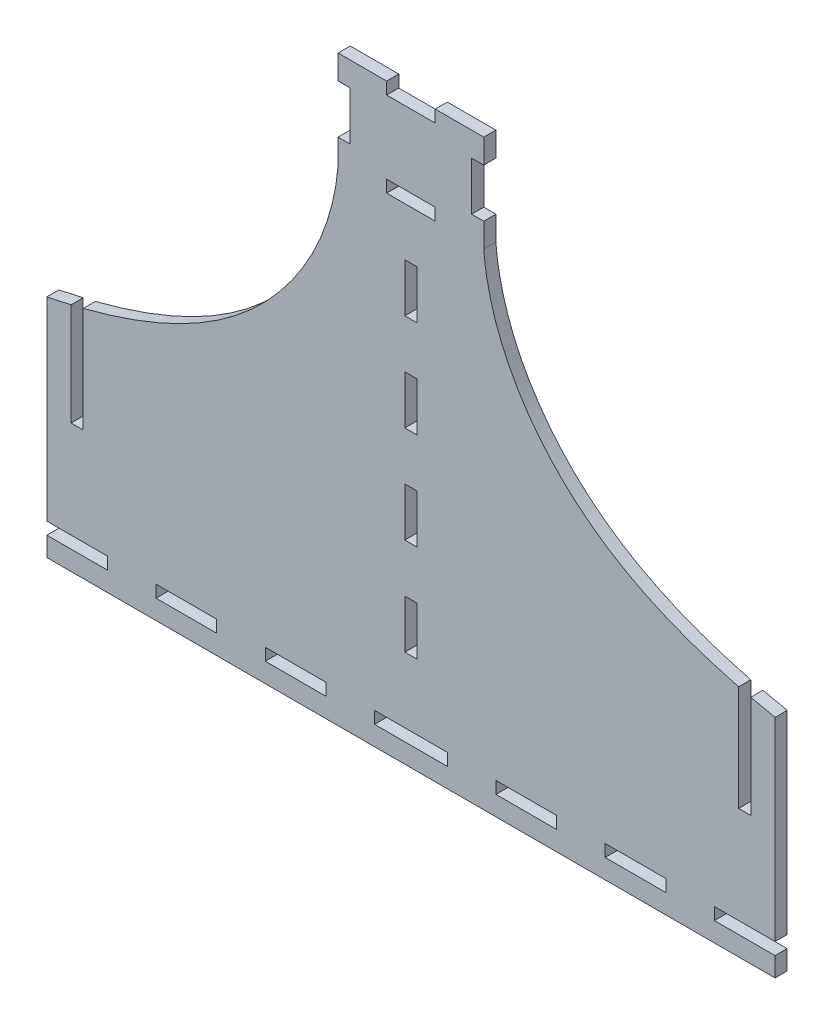
SolidWorks part; units mm, degrees
ref_plane "Front Plane" through (0, 0, 0) normal (0, 0, 1) x (1, 0, 0)
ref_plane "Top Plane" through (0, 0, 0) normal (0, 1, 0) x (1, 0, 0)
ref_plane "Right Plane" through (0, 0, 0) normal (1, 0, 0) x (0, 0, -1)
sketch "Sketch1" plane through (0, 0, 0) normal (0, 0, 1) x (1, 0, 0)
  line L0 (-39.7844, 125.4532) -> (-39.7844, 135.4532)
  line L1 (-39.7844, 165.4532) -> (-59.7844, 165.4532)
  line L2 (-99.7844, 125.4532) -> (-99.7844, 135.4532)
  line L3 (-79.7844, 165.4532) -> (-99.7844, 165.4532)
  line L5 (-79.7844, 165.4532) -> (-79.7844, 160.4532)
  line L6 (-79.7844, 160.4532) -> (-59.7844, 160.4532)
  line L7 (-59.7844, 165.4532) -> (-59.7844, 160.4532)
  line L8 (-69.7844, 165.4532) -> (-59.7844, 160.4532) construction
  line L9 (-79.7844, 160.4532) -> (-69.7844, 165.4532) construction
  line L10 (-39.7844, 155.4532) -> (-39.7844, 165.4532)
  line L11 (-39.7844, 155.4532) -> (-44.7844, 155.4532)
  line L13 (-39.7844, 135.4532) -> (-44.7844, 135.4532)
  line L14 (-44.7844, 155.4532) -> (-44.7844, 135.4532)
  line L15 (-94.7844, 155.4532) -> (-94.7844, 135.4532)
  line L16 (-99.7844, 135.4532) -> (-94.7844, 135.4532)
  line L17 (-99.7844, 155.4532) -> (-94.7844, 155.4532)
  line L18 (-99.7844, 155.4532) -> (-99.7844, 165.4532)
  line L19 (-94.7844, 145.4532) -> (-90.6665, 145.4532) construction
  line L20 (-79.7844, 130.4532) -> (-69.7844, 125.4532) construction
  line L21 (-69.7844, 125.4532) -> (-59.7844, 130.4532) construction
  line L22 (-59.7844, 125.4532) -> (-59.7844, 130.4532)
  line L23 (-79.7844, 130.4532) -> (-59.7844, 130.4532)
  line L24 (-79.7844, 125.4532) -> (-79.7844, 130.4532)
  line L25 (-79.7844, 125.4532) -> (-59.7844, 125.4532)
  line L26 (-72.2844, 65.4532) -> (-67.2844, 65.4532)
  line L27 (-72.2844, 105.4532) -> (-67.2844, 105.4532)
  line L28 (80.2156, -61.5468) -> (55.2156, -61.5468)
  line L29 (55.2156, -61.5468) -> (55.2156, -66.5468)
  line L30 (55.2156, -66.5468) -> (80.2156, -66.5468)
  line L32 (35.2156, -61.5468) -> (10.2156, -61.5468)
  line L33 (10.2156, -61.5468) -> (10.2156, -66.5468)
  line L34 (10.2156, -66.5468) -> (35.2156, -66.5468)
  line L35 (35.2156, -66.5468) -> (35.2156, -61.5468)
  line L36 (-9.7844, -61.5468) -> (-34.7844, -61.5468)
  line L37 (-34.7844, -61.5468) -> (-34.7844, -66.5468)
  line L38 (-34.7844, -66.5468) -> (-9.7844, -66.5468)
  line L39 (-9.7844, -66.5468) -> (-9.7844, -61.5468)
  line L40 (-54.7844, -61.5468) -> (-84.7844, -61.5468)
  line L41 (-84.7844, -61.5468) -> (-84.7844, -66.5468)
  line L42 (-84.7844, -66.5468) -> (-54.7844, -66.5468)
  line L43 (-54.7844, -66.5468) -> (-54.7844, -61.5468)
  line L44 (-104.7844, -61.5468) -> (-129.7844, -61.5468)
  line L45 (-129.7844, -61.5468) -> (-129.7844, -66.5468)
  line L46 (-129.7844, -66.5468) -> (-104.7844, -66.5468)
  line L47 (-104.7844, -66.5468) -> (-104.7844, -61.5468)
  line L48 (-149.7844, -61.5468) -> (-174.7844, -61.5468)
  line L49 (-174.7844, -61.5468) -> (-174.7844, -66.5468)
  line L50 (-174.7844, -66.5468) -> (-149.7844, -66.5468)
  line L51 (-149.7844, -66.5468) -> (-149.7844, -61.5468)
  line L52 (-194.7844, -61.5468) -> (-219.7844, -61.5468)
  line L54 (-219.7844, -66.5468) -> (-194.7844, -66.5468)
  line L55 (-194.7844, -66.5468) -> (-194.7844, -61.5468)
  line L56 (-69.7844, -61.5468) -> (-69.7844, -38.2904) construction
  line L57 (-219.7844, -66.5468) -> (-219.7844, -74.5468)
  line L59 (-219.7844, 18.4532) -> (-219.7844, -61.5468)
  line L60 (-219.7844, -74.5468) -> (80.2156, -74.5468)
  line L61 (80.2156, 18.4532) -> (80.2156, -61.5468)
  line L62 (80.2156, -66.5468) -> (80.2156, -74.5468)
  line L63 (-72.2844, 105.4532) -> (-72.2844, 85.4532)
  line L64 (-72.2844, 85.4532) -> (-67.2844, 85.4532)
  line L65 (-67.2844, 105.4532) -> (-67.2844, 85.4532)
  line L66 (-72.2844, 105.4532) -> (-67.2844, 85.4532) construction
  line L67 (-72.2844, 85.4532) -> (-67.2844, 105.4532) construction
  line L68 (-72.2844, 65.4532) -> (-72.2844, 45.4532)
  line L69 (-67.2844, 65.4532) -> (-67.2844, 45.4532)
  line L70 (-72.2844, 45.4532) -> (-67.2844, 45.4532)
  line L71 (-72.2844, 25.4532) -> (-67.2844, 25.4532)
  line L72 (-72.2844, 25.4532) -> (-72.2844, 5.4532)
  line L73 (-67.2844, 25.4532) -> (-67.2844, 5.4532)
  line L74 (-72.2844, 5.4532) -> (-67.2844, 5.4532)
  line L75 (-72.2844, -14.5468) -> (-67.2844, -14.5468)
  line L76 (-72.2844, -14.5468) -> (-72.2844, -34.5468)
  line L77 (-67.2844, -14.5468) -> (-67.2844, -34.5468)
  line L78 (-72.2844, -34.5468) -> (-67.2844, -34.5468)
  line L80 (70.2156, -21.5468) -> (65.2156, -21.5468)
  line L81 (65.2156, -21.5468) -> (65.2156, 21.8436)
  line L82 (70.2156, -21.5468) -> (70.2156, 20.6184)
  line L83 (-209.7844, -21.5468) -> (-209.7844, 20.6184)
  line L84 (-204.7844, -21.5468) -> (-204.7844, 21.8436)
  line L85 (-209.7844, -21.5468) -> (-204.7844, -21.5468)
  spline S0 degree 2 poles (80.2156, 18.4532) (75.2223, 19.4417) (70.2156, 20.6184) knots 0 0 0 0.059833 0.059833 0.059833
  spline S1 degree 2 poles (-219.7844, 18.4532) (-214.7911, 19.4417) (-209.7844, 20.6184) knots 0 0 0 0.059833 0.059833 0.059833
  spline S2 degree 3 poles (65.2156, 21.8436) (57.9374, 23.7019) (35.9058, 30.3485) (-11.4217, 54.2754) (-37.385, 95.2098) (-39.7844, 125.4532) knots 0.089716 0.089716 0.089716 0.089716 0.220284 0.486407 1 1 1 1
  spline S3 degree 3 poles (-204.7844, 21.8436) (-197.5062, 23.7019) (-175.4746, 30.3485) (-128.1471, 54.2754) (-102.1839, 95.2098) (-99.7844, 125.4532) knots 0.089716 0.089716 0.089716 0.089716 0.220284 0.486407 1 1 1 1
  point P14 (-69.7844, 165.4532)
  point P38 (0, 0)
  point P46 (-69.7844, 165.4532)
  point P66 (-69.7844, 125.4532)
  point P67 (-69.7844, 125.4532)
  point P68 (-69.7844, 95.4532)
  dimension "D1" = 300
  dimension "D2" = 8
  dimension "D3" = 80
  dimension "D4" = 40
  dimension "D5" = 30
  dimension "D6" = 240
  dimension "D7" = 20
  dimension "D8" = 5
  dimension "D9" = 5
  dimension "D10" = 20
  dimension "D11" = 10
  dimension "D12" = 25
  dimension "D13" = 10
  dimension "D14" = 5
  dimension "D15" = 20
  dimension "D17" = 20
  dimension "D18" = 20
  dimension "D19" = 5
  dimension "D20" = 40
  dimension "D21" = 10
  dimension "D22" = 80
  dimension "D23" = 25
  dimension "D16" = 4
extrude "Boss-Extrude1" add sketch "Sketch1" along normal blind 5
